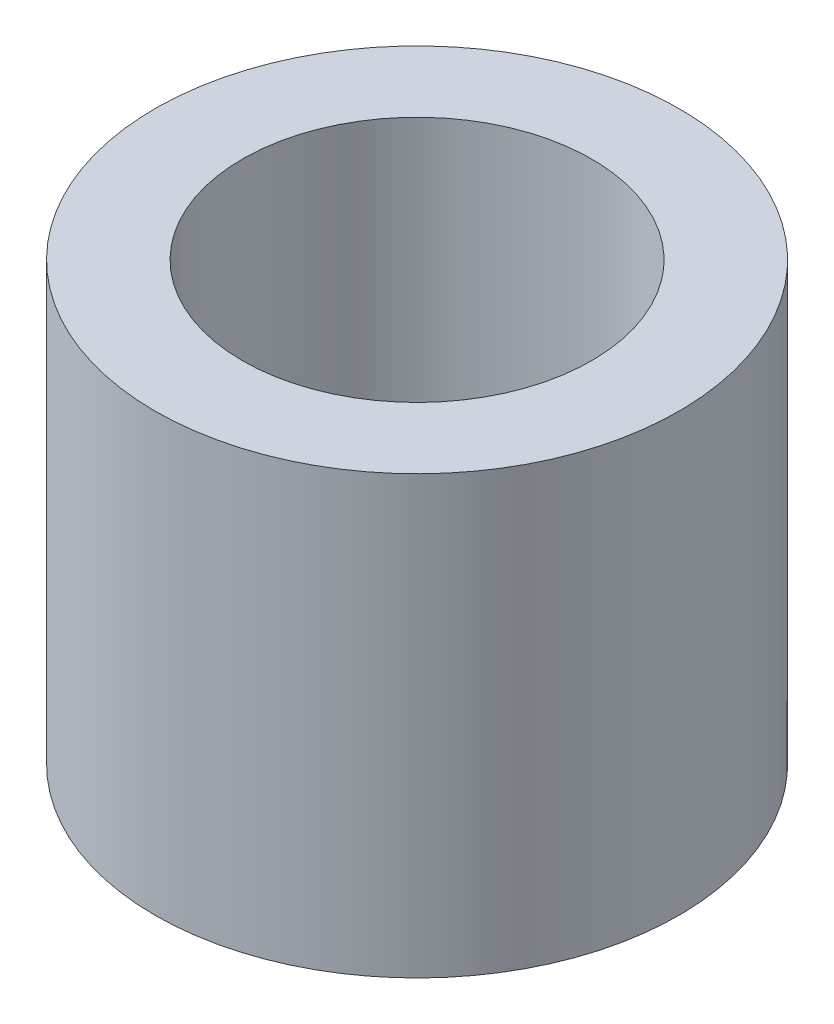
SolidWorks part; units mm, degrees
material "Brass"
ref_plane "Front Plane" through (0, 0, 0) normal (0, 0, 1) x (1, 0, 0)
ref_plane "Top Plane" through (0, 0, 0) normal (0, 1, 0) x (1, 0, 0)
ref_plane "Right Plane" through (0, 0, 0) normal (1, 0, 0) x (0, 0, -1)
sketch "Sketch1" plane through (0, 0, 0) normal (0, 1, 0) x (1, 0, 0)
  circle A0 centre (0, 0) radius 5.08
  circle A1 centre (0, 0) radius 7.62
  dimension "D1" = 10.16
  dimension "D2" = 2.54
extrude "Boss-Extrude1" add sketch "Sketch1" along normal blind 12.7
